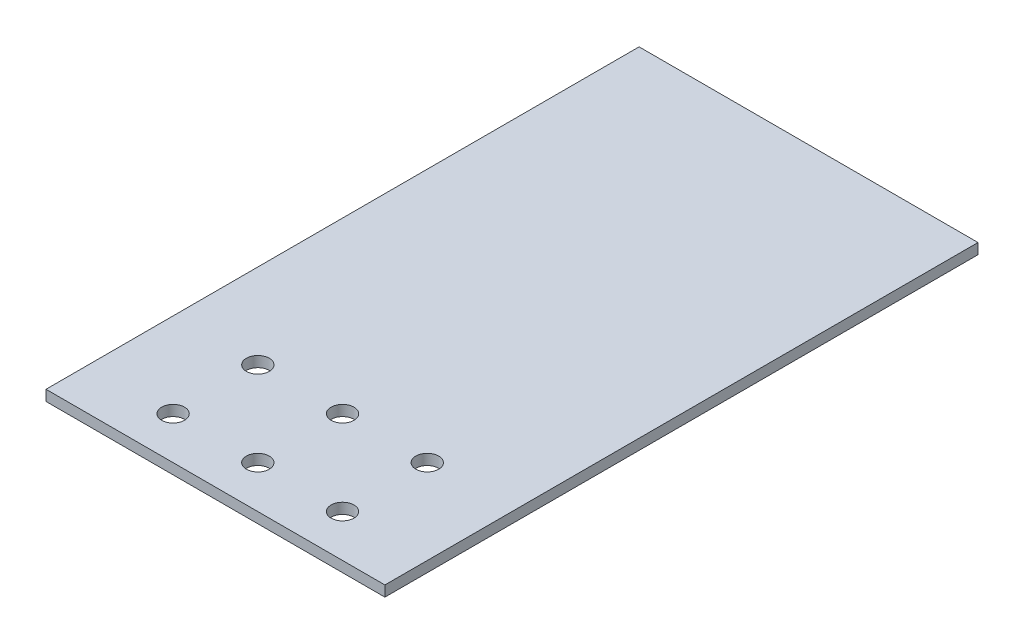
SolidWorks part; units mm, degrees
ref_plane "Front Plane" through (0, 0, 0) normal (0, 0, 1) x (1, 0, 0)
ref_plane "Top Plane" through (0, 0, 0) normal (0, 1, 0) x (1, 0, 0)
ref_plane "Right Plane" through (0, 0, 0) normal (1, 0, 0) x (0, 0, -1)
sketch "Sketch1" plane through (0, 0, 0) normal (0, 1, 0) x (1, 0, 0)
  line L1 (-50.8, -88.9) -> (50.8, -88.9)
  line L2 (-50.8, -88.9) -> (-50.8, 88.9)
  line L3 (-50.8, 88.9) -> (50.8, 88.9)
  line L4 (50.8, -88.9) -> (50.8, 88.9)
  line L5 (-50.8, -88.9) -> (50.8, 88.9) construction
  line L6 (-50.8, 88.9) -> (50.8, -88.9) construction
  circle A0 centre (-25.4, -76.2) radius 3.429
  circle A1 centre (0, -76.2) radius 3.429
  circle A2 centre (25.4, -76.2) radius 3.429
  circle A3 centre (0, -50.8) radius 3.429
  circle A4 centre (25.4, -50.8) radius 3.429
  circle A5 centre (-25.4, -50.8) radius 3.429
  point P0 (0, 0)
  dimension "D3" = 6.858
  dimension "D1" = 101.6
  dimension "D2" = 177.8
  dimension "D4" = 25.4
  dimension "D5" = 12.7
  dimension "D6" = 3
  dimension "D7" = 2
extrude "Boss-Extrude1" add sketch "Sketch1" along normal blind 3.175
